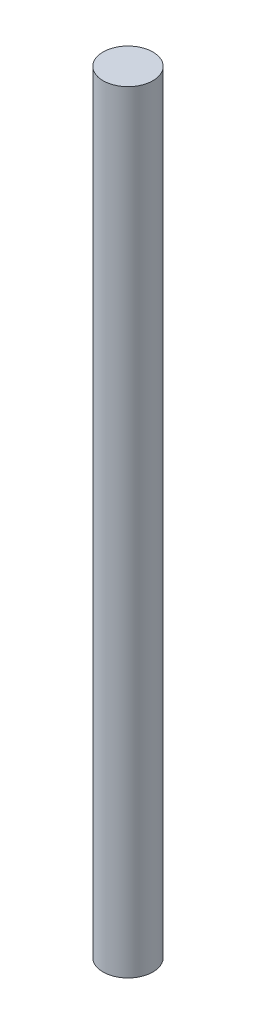
SolidWorks part; units mm, degrees
material "Acier non allié"
ref_plane "Plan de face" through (0, 0, 0) normal (0, 0, 1) x (1, 0, 0)
ref_plane "Plan de dessus" through (0, 0, 0) normal (0, 1, 0) x (1, 0, 0)
ref_plane "Plan de droite" through (0, 0, 0) normal (1, 0, 0) x (0, 0, -1)
sketch "Esquisse1" plane through (0, 0, 0) normal (0, 1, 0) x (1, 0, 0)
  circle A0 centre (0, 0) radius 2
extrude "Boss.-Extru.1" add sketch "Esquisse1" along normal blind 62
